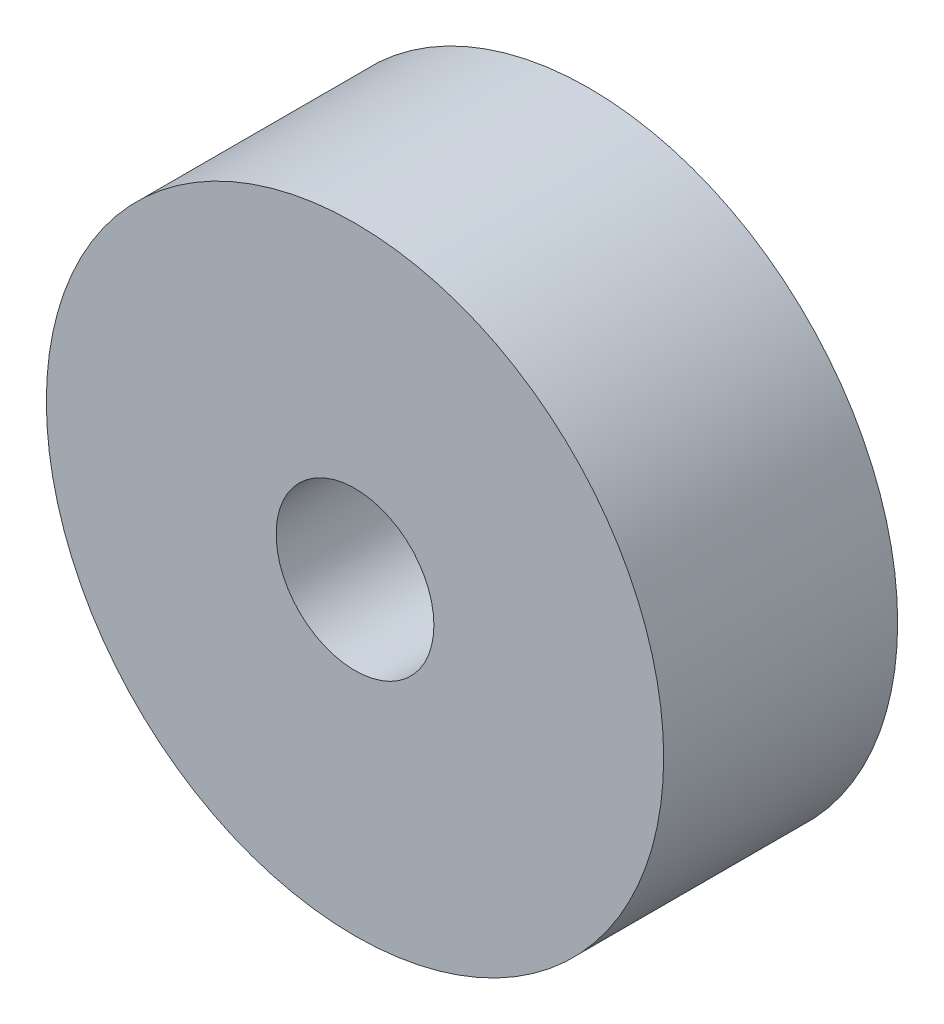
SolidWorks part; units mm, degrees
ref_plane "Front Plane" through (0, 0, 0) normal (0, 0, 1) x (1, 0, 0)
ref_plane "Top Plane" through (0, 0, 0) normal (0, 1, 0) x (1, 0, 0)
ref_plane "Right Plane" through (0, 0, 0) normal (1, 0, 0) x (0, 0, -1)
sketch "Sketch1" plane through (0, 0, 0) normal (0, 0, 1) x (1, 0, 0)
  line L0 (55, 0) -> (-55, 0) construction
  circle A0 centre (0, 0) radius 1.61
  circle A1 centre (0, 0) radius 6.2992
  dimension "D1" = 3.22
  dimension "D2" = 12.5984
extrude "Boss-Extrude1" add sketch "Sketch1" along normal blind 4.7752
